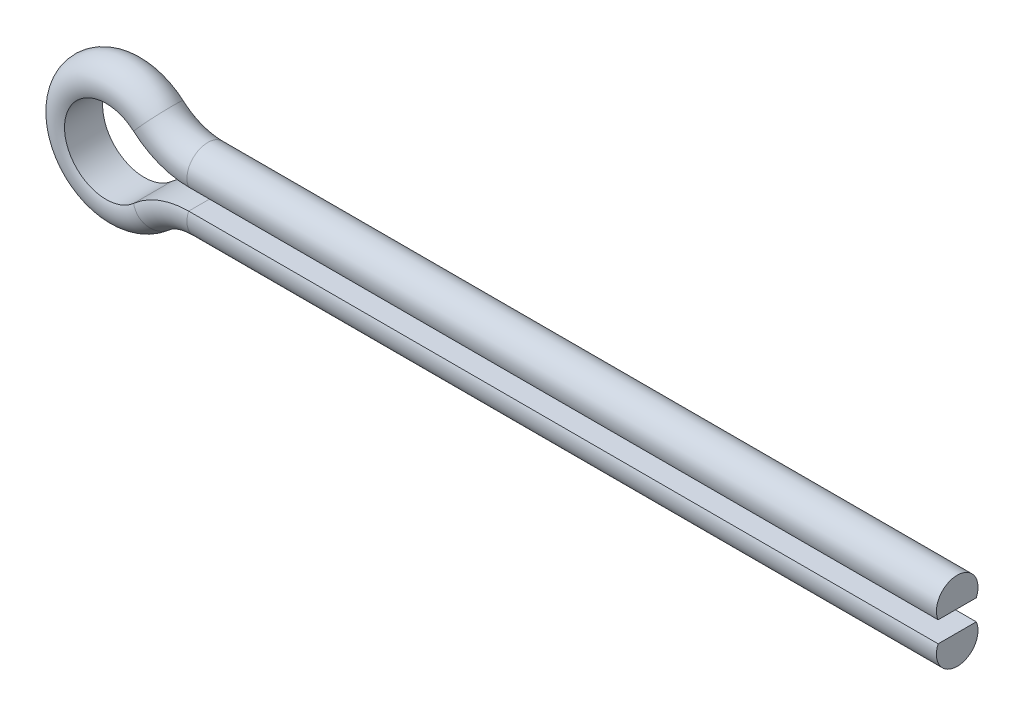
SolidWorks part; units mm, degrees
ref_plane "Front Plane" through (0, 0, 0) normal (0, 0, 1) x (1, 0, 0)
ref_plane "Top Plane" through (0, 0, 0) normal (0, 1, 0) x (1, 0, 0)
ref_plane "Right Plane" through (0, 0, 0) normal (1, 0, 0) x (0, 0, -1)
sketch "Sketch1" plane through (0, 0, 0) normal (0, 0, 1) x (1, 0, 0)
  line L0 (0, 0) -> (33.2669, 0) construction
  line L1 (9.9216, 1.25) -> (100, 1.25)
  line L2 (9.9216, -1.25) -> (100, -1.25)
  arc A0 (3.3072, 3.75) -> (3.3072, -3.75) centre (0, 0) ccw
  arc A1 (9.9216, -1.25) -> (3.3072, -3.75) centre (9.9216, -11.25) ccw
  arc A2 (9.9216, 1.25) -> (3.3072, 3.75) centre (9.9216, 11.25) cw
  point P9 (4.8412, -1.25)
  point P12 (4.8412, 1.25)
  dimension "D1" = 10
  dimension "D3" = 10
  dimension "D2" = 100
  dimension "D4" = 2.5
ref_plane "Plane1" through (100, 1.25, 0) normal (1, 0, 0) x (0, 0, -1)
sketch "Sketch2" plane through (100, 1.25, 0) normal (1, 0, 0) x (0, 0, -1)
  line L0 (-2.2913, 0) -> (2.2913, 0)
  line L1 (0, 3.75) -> (0, -6.25) construction
  arc A0 (2.2913, 0) -> (-2.2913, 0) centre (0, 1) ccw
  dimension "D1" = 5
  dimension "D2" = 1
sweep "Sweep1" add profiles "Sketch2" path "Sketch1"
